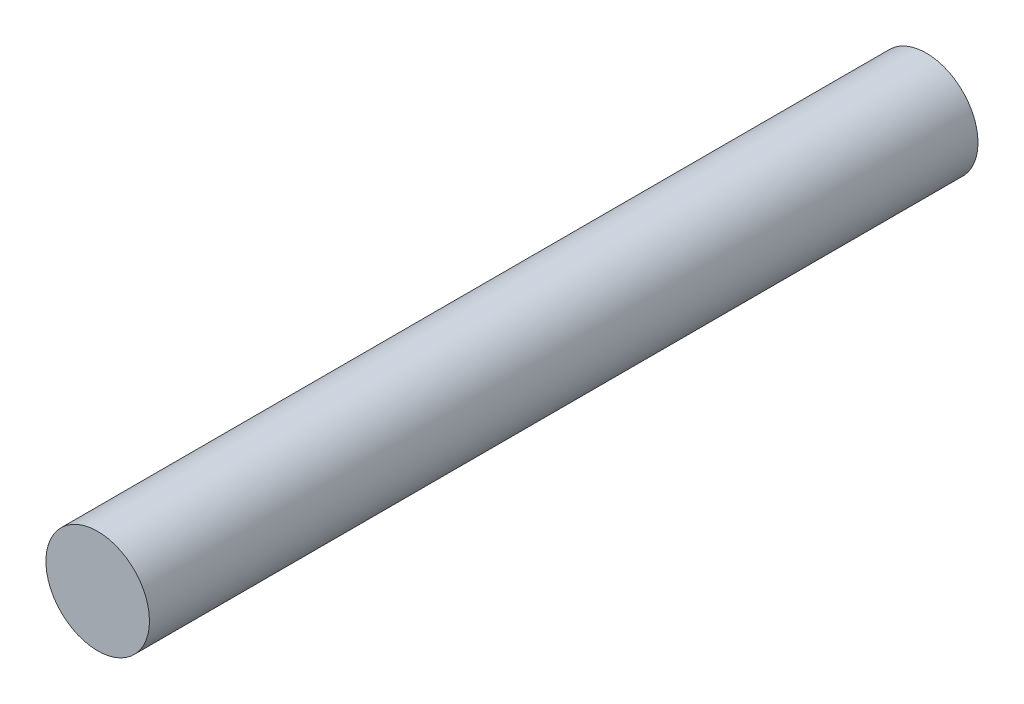
SolidWorks part; units mm, degrees
ref_plane "Front Plane" through (0, 0, 0) normal (1, 0, 0) x (0, 1, 0)
ref_plane "Top Plane" through (0, 0, 0) normal (0, 0, 1) x (0, 1, 0)
ref_plane "Right Plane" through (0, 0, 0) normal (0, 1, 0) x (-1, 0, 0)
sketch "Sketch1" plane through (0, 0, 0) normal (0, 0, 1) x (0, 1, 0)
  circle A0 centre (0, 0) radius 1.5875
  dimension "D1" = 3.175
extrude "Boss-Extrude1" add sketch "Sketch1" along normal blind 25.4 contours A0
